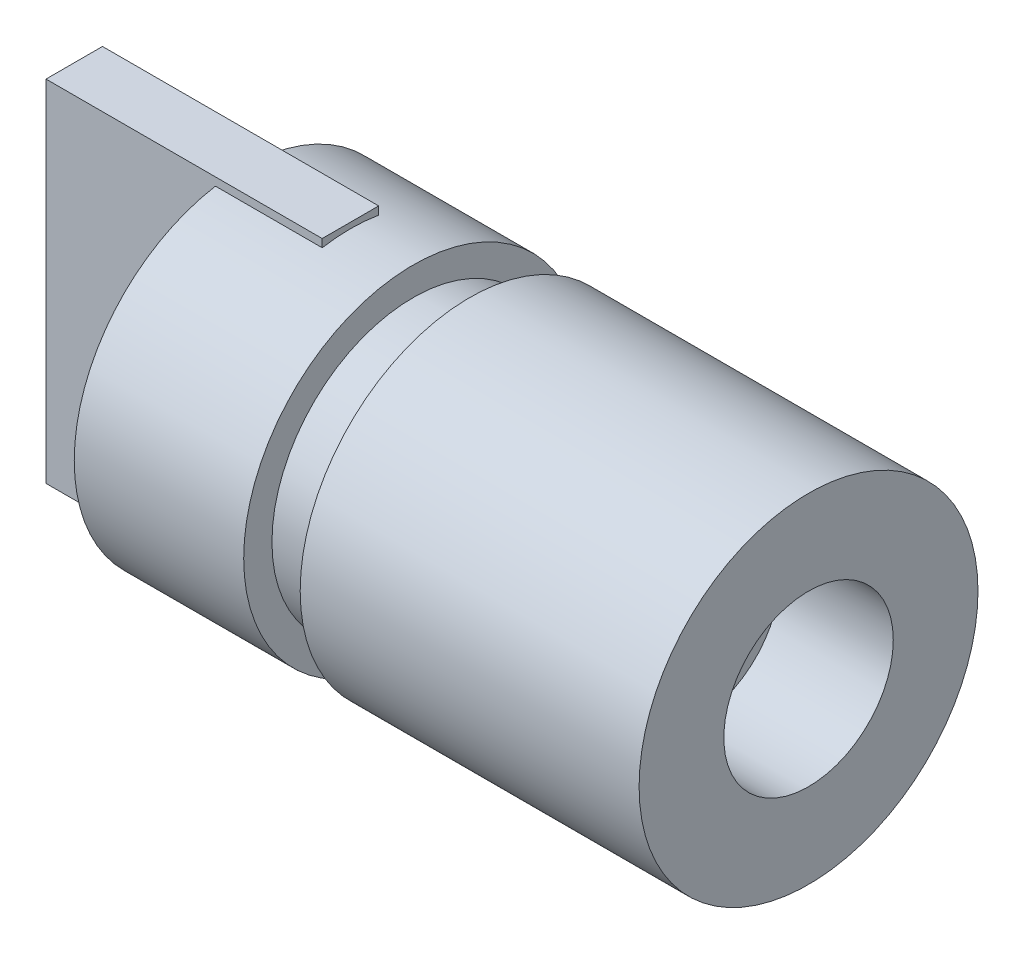
SolidWorks part; units mm, degrees
ref_plane "Спереди" through (0, 0, 0) normal (0, 0, 1) x (1, 0, 0)
ref_plane "Сверху" through (0, 0, 0) normal (0, 1, 0) x (1, 0, 0)
ref_plane "Справа" through (0, 0, 0) normal (1, 0, 0) x (0, 0, -1)
sketch "Эскиз1" plane through (0, 0, 0) normal (1, 0, 0) x (0, 0, -1)
  circle A0 centre (0, 0) radius 3
  dimension "D1" = 6
extrude "Бобышка-Вытянуть1" add sketch "Эскиз1" along normal blind 10
sketch "Эскиз2" plane through (0, 0, 0) normal (0, 0, 1) x (1, 0, 0)
  line L0 (3, 3) -> (3, 2.5)
  line L1 (10, 3) -> (0, 3) construction
  line L2 (3, 2.5) -> (4, 2.5)
  line L3 (4, 2.5) -> (4, 3)
  line L4 (3, 3) -> (4, 3)
  line L5 (-1000, 0) -> (49000, 0) construction
  line L6 (10, -3) -> (10, 3) construction
  dimension "D1" = 2.5
  dimension "D2" = 6
  dimension "D3" = 1
revolve "Вырез-Повернуть1" cut sketch "Эскиз2" angle 360 about L5
sketch "Эскиз3" plane through (10, 0, 0) normal (1, 0, 0) x (0, 0, -1)
  circle A0 centre (0, 0) radius 1.5
  dimension "D1" = 3
extrude "Вырез-Вытянуть1" cut sketch "Эскиз3" against normal blind 2
sketch "Эскиз4" plane through (0, 0, 0) normal (0, 0, 1) x (1, 0, 0)
  line L0 (1.8897, 3.1) -> (-3, 3.1)
  line L1 (-3, 3.1) -> (-3, -3.1)
  line L2 (-3, -3.1) -> (1.8897, -3.1)
  line L4 (1.8897, -3.1) -> (1.8897, 3.1)
  line L5 (10, -3) -> (10, 3) construction
  line L6 (-1000, 0) -> (49000, 0) construction
  dimension "D1" = 13
  dimension "D2" = 3.1
  dimension "D3" = 3.1
extrude "Бобышка-Вытянуть2" add sketch "Эскиз4" along normal mid plane 1
